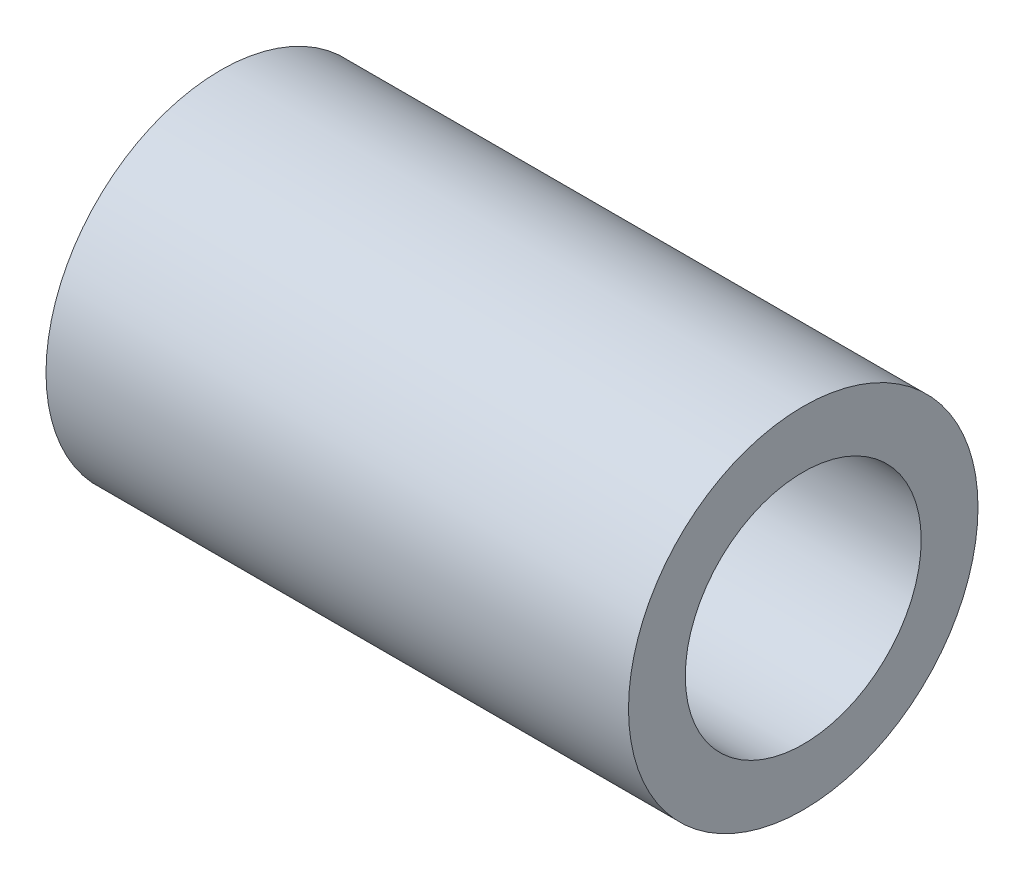
SolidWorks part; units mm, degrees
other "Preload Acetal Guide Bush"
ref_plane "Front Plane" through (0, 0, 0) normal (0, 0, 1) x (1, 0, 0)
ref_plane "Top Plane" through (0, 0, 0) normal (0, 1, 0) x (1, 0, 0)
ref_plane "Right Plane" through (0, 0, 0) normal (1, 0, 0) x (0, 0, -1)
sketch3d "Acetal guide sleeve outside sketch datum points"
  point P0 (28.7083, -9, -28)
  point P1 (28.7083, 1, -28)
  point P2 (28.7083, -9, -18)
ref_plane "Acetal guide sleeve outside sketch plane" through (28.7083, 0, 0) normal (1, 0, 0) x (0, 0, -1)
sketch "Acetal guide sleeve outside sketch" plane through (28.7083, 0, 0) normal (1, 0, 0) x (0, 0, -1)
  circle A0 centre (28, -9) radius 6
extrude "Acetal guide sleeve outside" add sketch "Acetal guide sleeve outside sketch" along normal blind 20 separate body
sketch3d "Acetal guide sleeve bore sketch datum points"
  point P0 (28.6083, -9, -28)
  point P1 (28.6083, 1, -28)
  point P2 (28.6083, -9, -18)
ref_plane "Acetal guide sleeve bore sketch plane" through (28.6083, 0, 0) normal (1, 0, 0) x (0, 0, -1)
sketch "Acetal guide sleeve bore sketch" plane through (28.6083, 0, 0) normal (1, 0, 0) x (0, 0, -1)
  circle A0 centre (28, -9) radius 4.05
extrude "Acetal guide sleeve bore" cut sketch "Acetal guide sleeve bore sketch" along normal blind 20.2
